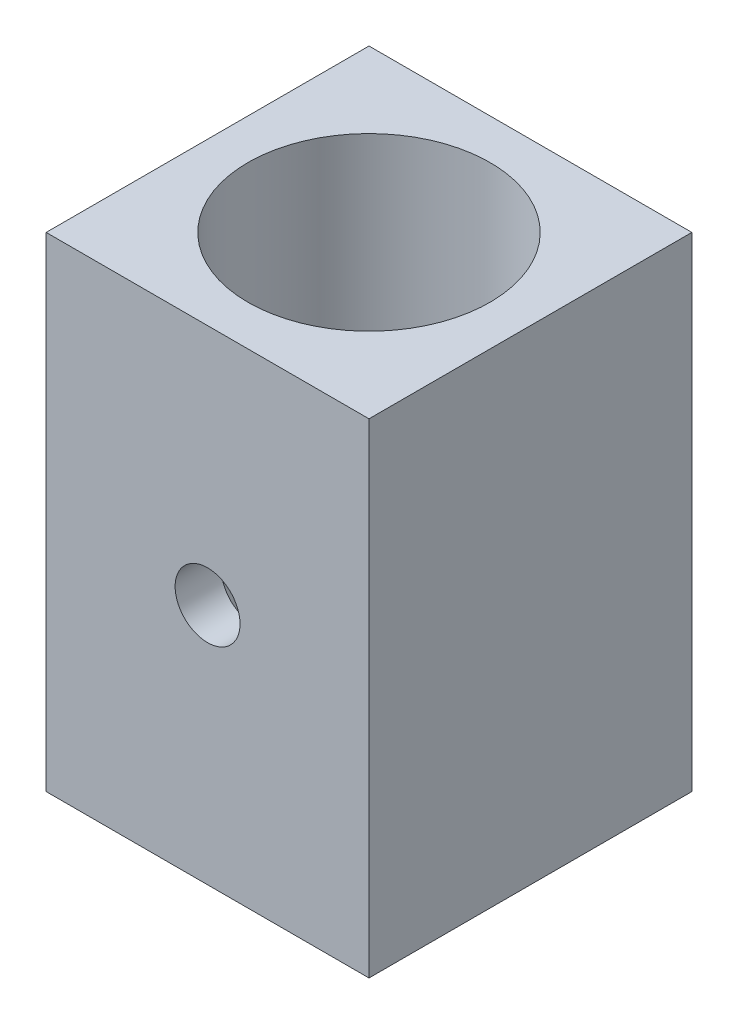
SolidWorks part; units mm, degrees
ref_plane "Front Plane" through (0, 0, 0) normal (0, 0, 1) x (1, 0, 0)
ref_plane "Top Plane" through (0, 0, 0) normal (0, 1, 0) x (1, 0, 0)
ref_plane "Right Plane" through (0, 0, 0) normal (1, 0, 0) x (0, 0, -1)
sketch "Sketch1" plane through (0, 0, 0) normal (0, 1, 0) x (1, 0, 0)
  line L0 (0, 25.4) -> (25.4, 0) construction
  line L1 (0, 0) -> (25.4, 0)
  line L2 (0, 0) -> (0, 25.4)
  line L3 (0, 25.4) -> (25.4, 25.4)
  line L4 (25.4, 0) -> (25.4, 25.4)
  circle A0 centre (12.7, 12.7) radius 9.525
  dimension "D3" = 19.05
  dimension "D1" = 25.4
  dimension "D2" = 25.4
extrude "Boss-Extrude1" add sketch "Sketch1" along normal blind 38.1
hole_wizard "Tap Drill for 1/4-20 Tap1" positions "Sketch2" profile "Sketch3" hole size "1/4-20" standard "ANSI Inch"
sketch "Sketch2" plane through (0, 0, 0) normal (0, 0, 1) x (1, 0, 0)
  line L0 (0, 38.1) -> (0, 0) construction
  point P0 (12.7, 19.05)
  dimension "D1" = 19.05
  dimension "D2" = 12.7
sketch "Sketch3" plane through (12.7, 19.05, 0) normal (1, 0, 0) x (0, -1, 0)
  line L0 (0, 0) -> (0, 3.175)
  line L1 (0, 3.175) -> (2.5527, 3.175)
  line L2 (2.5527, 3.175) -> (2.5527, 0)
  line L5 (2.5527, 0) -> (0, 0)
  line L11 (0, -6.35) -> (0, 107.95) construction
  dimension "Thru Hole Dia." = 5.1054
  dimension "Thru Hole Depth" = 3.175
